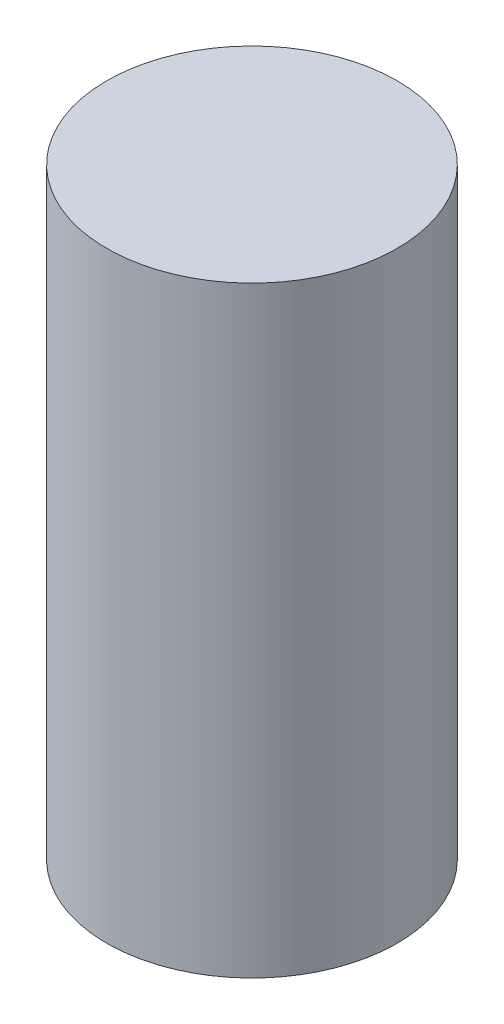
SolidWorks part; units mm, degrees
ref_plane "Front Plane" through (0, 0, 0) normal (0, 0, 1) x (1, 0, 0)
ref_plane "Top Plane" through (0, 0, 0) normal (0, 1, 0) x (1, 0, 0)
ref_plane "Right Plane" through (0, 0, 0) normal (1, 0, 0) x (0, 0, -1)
sketch "Sketch1" plane through (0, 0, 0) normal (0, 1, 0) x (1, 0, 0)
  circle A0 centre (0, 0) radius 12.5
  dimension "D1" = 25
extrude "Boss-Extrude1" add sketch "Sketch1" along normal blind 51.8
